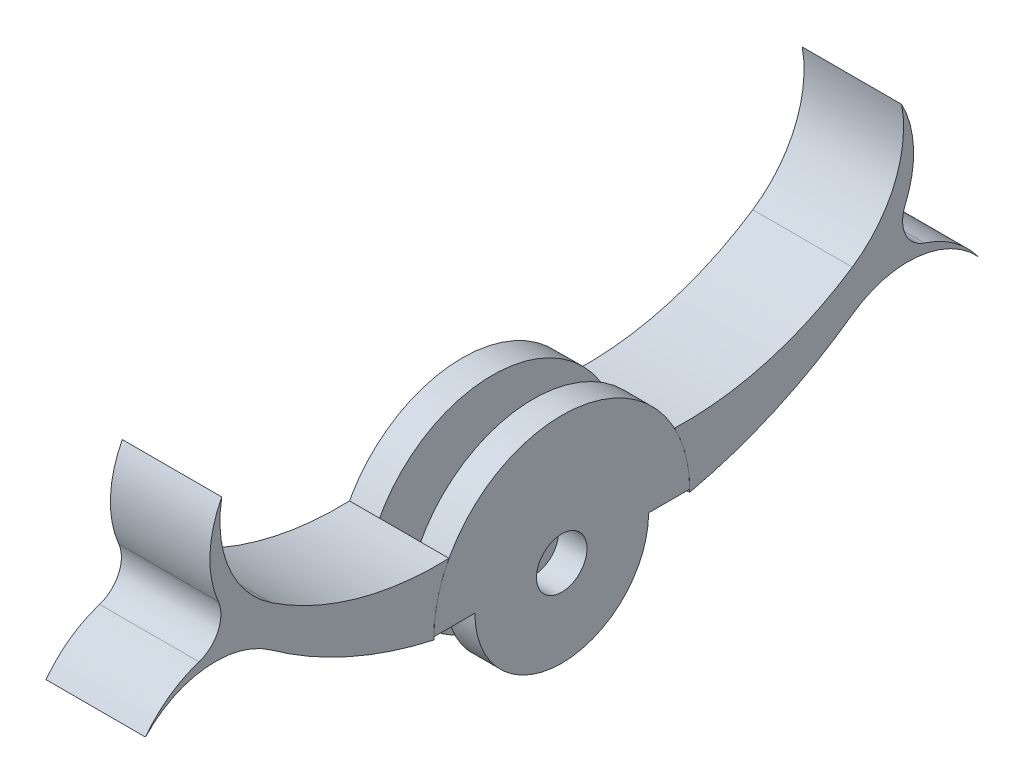
SolidWorks part; units mm, degrees
material "PVC Rigid"
ref_plane "Front Plane" through (0, 0, 0) normal (0, 0, 1) x (1, 0, 0)
ref_plane "Top Plane" through (0, 0, 0) normal (0, 1, 0) x (1, 0, 0)
ref_plane "Right Plane" through (0, 0, 0) normal (1, 0, 0) x (0, 0, -1)
sketch "Sketch1" plane through (0, 0, 0) normal (1, 0, 0) x (0, 0, -1)
  circle A0 centre (0, 0) radius 10.287
  dimension "D1" = 20.574
extrude "Boss-Extrude1" add sketch "Sketch1" along normal blind 8.001
sketch "Sketch2" plane through (8.001, 0, 0) normal (1, 0, 0) x (0, 0, -1)
  circle A0 centre (0, 0) radius 2.032
  dimension "D1" = 4.064
extrude "Cut-Extrude1" cut sketch "Sketch2" against normal blind 3.7338
sketch "Sketch3" plane through (0, 0, 0) normal (-1, 0, 0) x (0, 0, 1)
  circle A0 centre (0, 0) radius 2.032
  dimension "D1" = 4.064
extrude "Cut-Extrude2" cut sketch "Sketch3" against normal blind 3.7338
sketch "Sketch4" plane through (0, 0, 0) normal (-1, 0, 0) x (0, 0, 1)
  arc A0 (9.0665, 4.8601) -> (10.2846, -0.2199) centre (0, 0) cw
  arc A1 (10.2846, -0.2199) -> (23.3656, 5.6221) centre (2.5819, 34.5935) ccw
  circle A2 centre (0, 0) radius 10.287 construction
  arc A3 (9.0665, 4.8601) -> (23.3656, 8.9241) centre (9.8998, 29.1159) ccw
  arc A4 (23.3656, 8.9241) -> (27.3418, 18.2737) centre (18.2267, 16.6299) ccw
  arc A5 (27.3418, 18.2737) -> (27.6197, 11.1275) centre (20.0122, 14.4102) cw
  arc A6 (23.3656, 5.6221) -> (33.4757, 4.6157) centre (27.8487, -0.6271) cw
  arc A7 (33.4757, 4.6157) -> (29.1713, 7.7042) centre (26.5027, -0.5588) ccw
  arc A8 (27.6197, 11.1275) -> (29.1713, 7.7042) centre (29.9519, 10.1212) ccw
  dimension "D8" = 2.54
  dimension "D1" = 13.081
  dimension "D2" = 5.842
  dimension "D3" = 5.08
  dimension "D4" = 3.302
  dimension "D5" = 0
  dimension "D6" = 10.16
  dimension "D7" = 10.16
extrude "Boss-Extrude2" add sketch "Sketch4" against normal up to surface (8.001 mm away) separate body up to face at (8.001, 0, -2.032)
mirror "Mirror3" about plane through (0, 0, 0) normal (0, 0, 1) of bodies 104
sketch "Sketch5" plane through (8.001, 0, 0) normal (1, 0, 0) x (0, 0, -1)
  line L0 (-6.985, 0) -> (-10.287, 0)
  line L1 (6.985, 0) -> (10.287, 0)
  arc A0 (6.985, 0) -> (-6.985, 0) centre (0, 0) cw
  circle A1 centre (0, 0) radius 10.287 construction
  arc A2 (10.2846, -0.2199) -> (9.0665, 4.8601) centre (0, 0) ccw construction
  arc A3 (-10.287, 0) -> (10.287, 0) centre (0, 0) ccw
  dimension "D1" = 6.985
extrude "Cut-Extrude3" cut sketch "Sketch5" against normal up to surface (8.001 mm away) up to face at (0, 0, 2.032)
ref_plane "Plane1" through (0, 10.287, 0) normal (0, 1, 0) x (1, 0, 0)
sketch "Sketch6" plane through (0, 10.287, 0) normal (0, 1, 0) x (1, 0, 0)
  line L1 (5.715, -9.9568) -> (2.413, -9.9568)
  line L2 (5.715, -9.9568) -> (5.715, 9.9568)
  line L3 (5.715, 9.9568) -> (2.413, 9.9568)
  line L4 (2.413, -9.9568) -> (2.413, 9.9568)
  line L5 (5.715, -9.9568) -> (2.413, 9.9568) construction
  line L6 (5.715, 9.9568) -> (2.413, -9.9568) construction
  point P0 (4.064, 0)
  dimension "D1" = 4.064
  dimension "D2" = 3.302
  dimension "D3" = 19.9136
extrude "Cut-Extrude4" cut sketch "Sketch6" against normal through all
